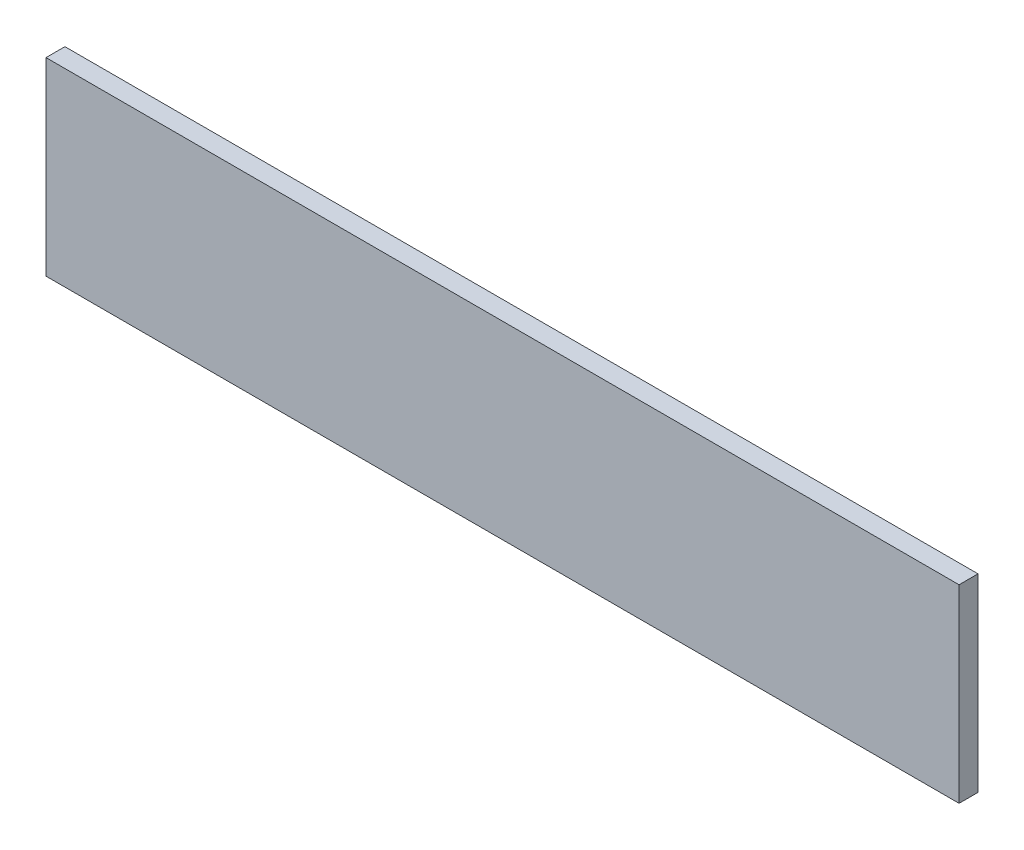
SolidWorks part; units mm, degrees
ref_plane "Front Plane" through (0, 0, 0) normal (0, 0, 1) x (1, 0, 0)
ref_plane "Top Plane" through (0, 0, 0) normal (0, 1, 0) x (1, 0, 0)
ref_plane "Right Plane" through (0, 0, 0) normal (1, 0, 0) x (0, 0, -1)
sketch "Sketch1" plane through (0, 0, 0) normal (0, 0, 1) x (1, 0, 0)
  line L0 (0, 0) -> (0, 10)
  line L1 (0, 10) -> (48.23, 10)
  line L2 (48.23, 10) -> (48.23, 0)
  line L3 (48.23, 0) -> (0, 0)
  dimension "D1" = 10
  dimension "D2" = 48.23
extrude "Boss-Extrude1" add sketch "Sketch1" along normal blind 1
